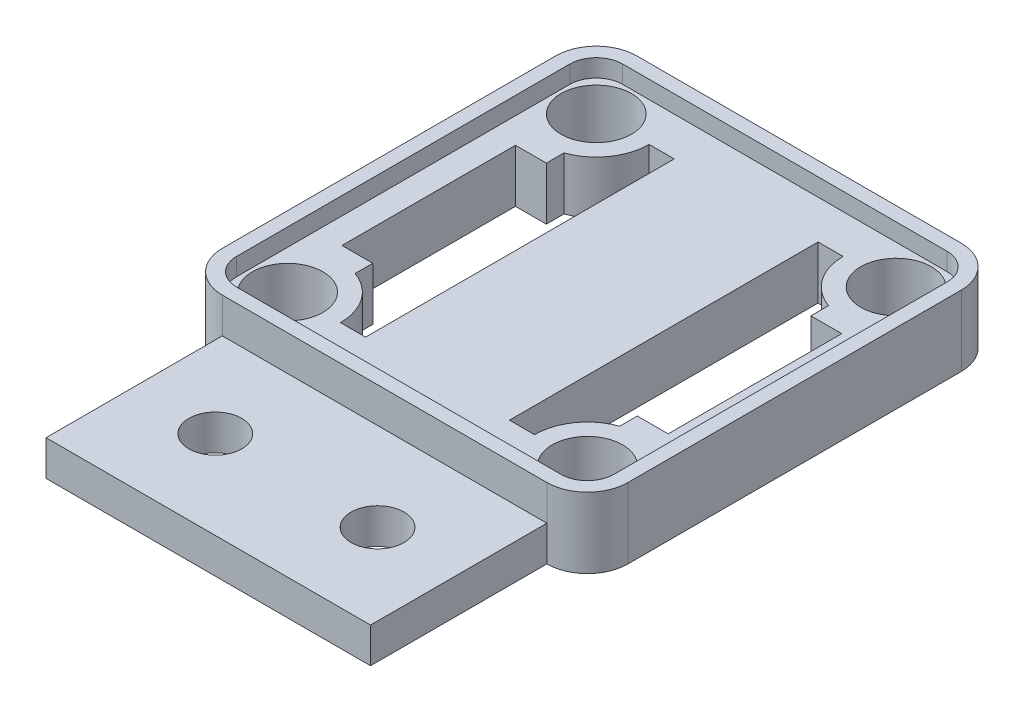
SolidWorks part; units mm, degrees
ref_plane "Front Plane" through (0, 0, 0) normal (0, 0, 1) x (1, 0, 0)
ref_plane "Top Plane" through (0, 0, 0) normal (0, 1, 0) x (1, 0, 0)
ref_plane "Right Plane" through (0, 0, 0) normal (1, 0, 0) x (0, 0, -1)
sketch "Sketch1" plane through (0, 0, 0) normal (0, 1, 0) x (1, 0, 0)
  line L1 (-12.6491, 14.6331) -> (5.7509, 14.6331)
  line L2 (-14.9491, 12.3331) -> (-14.9491, -6.5669)
  line L3 (-12.6491, -8.8669) -> (5.7509, -8.8669)
  line L4 (8.0509, 12.3331) -> (8.0509, -6.5669)
  line L5 (-14.9491, 14.6331) -> (8.0509, -8.8669) construction
  line L6 (-14.9491, -8.8669) -> (8.0509, 14.6331) construction
  arc A0 (8.0509, 12.3331) -> (5.7509, 14.6331) centre (5.7509, 12.3331) ccw
  arc A1 (-12.6491, -8.8669) -> (-14.9491, -6.5669) centre (-12.6491, -6.5669) cw
  arc A2 (5.7509, -8.8669) -> (8.0509, -6.5669) centre (5.7509, -6.5669) ccw
  arc A3 (-14.9491, 12.3331) -> (-12.6491, 14.6331) centre (-12.6491, 12.3331) cw
  point P0 (-3.4491, 2.8831)
  dimension "D3" = 2.3
  dimension "D4" = 2.3
  dimension "D1" = 23.5
  dimension "D2" = 23
extrude "Boss-Extrude1" add sketch "Sketch1" along normal blind 4
sketch "Sketch2" plane through (0, 4, 0) normal (0, 1, 0) x (1, 0, 0)
  line L8 (5.7509, 13.6331) -> (-12.6491, 13.6331)
  line L9 (-13.9491, 12.3331) -> (-13.9491, -6.5669)
  line L10 (-12.6491, -7.8669) -> (5.7509, -7.8669)
  line L11 (7.0509, -6.5669) -> (7.0509, 12.3331)
  line L12 (5.7509, 13.6331) -> (-12.6491, 13.6331)
  line L13 (-13.9491, 12.3331) -> (-13.9491, -6.5669)
  line L14 (-12.6491, -7.8669) -> (5.7509, -7.8669)
  line L15 (7.0509, -6.5669) -> (7.0509, 12.3331)
  arc A8 (7.0509, 12.3331) -> (5.7509, 13.6331) centre (5.7509, 12.3331) ccw
  arc A9 (-12.6491, 13.6331) -> (-13.9491, 12.3331) centre (-12.6491, 12.3331) ccw
  arc A10 (-13.9491, -6.5669) -> (-12.6491, -7.8669) centre (-12.6491, -6.5669) ccw
  arc A11 (5.7509, -7.8669) -> (7.0509, -6.5669) centre (5.7509, -6.5669) ccw
  arc A12 (7.0509, 12.3331) -> (5.7509, 13.6331) centre (5.7509, 12.3331) ccw
  arc A13 (-12.6491, 13.6331) -> (-13.9491, 12.3331) centre (-12.6491, 12.3331) ccw
  arc A14 (-13.9491, -6.5669) -> (-12.6491, -7.8669) centre (-12.6491, -6.5669) ccw
  arc A15 (5.7509, -7.8669) -> (7.0509, -6.5669) centre (5.7509, -6.5669) ccw
  dimension "D1" = 1
extrude "Cut-Extrude2" cut sketch "Sketch2" against normal blind 1
sketch "Sketch5" plane through (0, 3, 0) normal (0, 1, 0) x (1, 0, 0)
  line L0 (-3.4491, 13.6331) -> (-3.4491, -7.8669) construction
  line L1 (5.7509, 13.6331) -> (-12.6491, 13.6331) construction
  line L2 (-12.6491, -7.8669) -> (5.7509, -7.8669) construction
  line L3 (7.0509, 2.8831) -> (-13.9491, 2.8831) construction
  line L4 (7.0509, -6.5669) -> (7.0509, 12.3331) construction
  line L5 (-13.9491, 12.3331) -> (-13.9491, -6.5669) construction
  circle A0 centre (5.0509, 11.6331) radius 2
  circle A1 centre (5.0509, -5.8669) radius 2
  circle A2 centre (-11.9491, -5.8669) radius 2
  circle A3 centre (-11.9491, 11.6331) radius 2
  dimension "D1" = 4
extrude "Cut-Extrude3" cut sketch "Sketch5" against normal through all
sketch "Sketch6" plane through (0, 3, 0) normal (0, 1, 0) x (1, 0, 0)
  line L0 (-14.9491, 12.3331) -> (-14.9491, -6.5669) construction
  line L1 (8.0509, -6.5669) -> (8.0509, 12.3331) construction
  line L14 (4.0509, -5.8669) -> (4.0509, 11.6331)
  line L15 (4.0509, -3.0385) -> (4.0509, 8.8047)
  line L16 (2.0509, 11.6331) -> (2.0509, -5.8669)
  line L17 (-10.9491, 12.3331) -> (-10.9491, -6.5669)
  line L18 (-10.9491, 8.8047) -> (-10.9491, -3.0385)
  line L19 (-8.9491, 11.6331) -> (-8.9491, -5.8669)
  arc A5 (-11.9491, -8.8669) -> (-14.9491, -5.8669) centre (-11.9491, -5.8669) ccw
  arc A6 (-8.9491, -5.8669) -> (-10.9491, -3.0385) centre (-11.9491, -5.8669) ccw
  arc A20 (5.0509, 14.6331) -> (8.0509, 11.6331) centre (5.0509, 11.6331) ccw
  arc A21 (2.0509, 11.6331) -> (4.0509, 8.8047) centre (5.0509, 11.6331) ccw
  arc A23 (-14.9491, 11.6331) -> (-11.9491, 14.6331) centre (-11.9491, 11.6331) ccw
  arc A24 (-10.9491, 8.8047) -> (-8.9491, 11.6331) centre (-11.9491, 11.6331) ccw
  arc A26 (8.0509, -5.8669) -> (5.0509, -8.8669) centre (5.0509, -5.8669) ccw
  arc A27 (4.0509, -3.0385) -> (2.0509, -5.8669) centre (5.0509, -5.8669) ccw
  dimension "D1" = 23
  dimension "D2" = 1
  dimension "D3" = 1
  dimension "D4" = 1
  dimension "D5" = 1
  dimension "D6" = 3
  dimension "D7" = 3
extrude "Cut-Extrude4" cut sketch "Sketch6" against normal through all
sketch "Sketch7" plane through (0, 0, 8.8669) normal (0, 0, 1) x (1, 0, 0)
  line L0 (-14.9491, 4) -> (-14.9491, 0) construction
  line L1 (8.0509, 4) -> (8.0509, 0) construction
  line L2 (-12.6491, 4) -> (-12.6491, 0) construction
  line L3 (-12.6491, 2) -> (5.7509, 2)
  line L4 (5.7509, 4) -> (5.7509, 0) construction
  line L5 (5.7509, 2) -> (5.7509, 0)
  line L6 (5.7509, 0) -> (-12.6491, 0)
  line L7 (-12.6491, 0) -> (-12.6491, 2)
  dimension "D1" = 23
extrude "Boss-Extrude2" add sketch "Sketch7" along normal blind 10
sketch "Sketch8" plane through (0, 2, 0) normal (0, 1, 0) x (1, 0, 0)
  line L0 (-12.6491, -8.8669) -> (5.7509, -8.8669) construction
  line L1 (-12.6491, -18.8669) -> (-12.6491, -8.8669) construction
  line L2 (5.7509, -18.8669) -> (5.7509, -8.8669) construction
  line L3 (-3.4491, -8.8669) -> (-3.4491, -18.8669) construction
  line L4 (5.7509, -18.8669) -> (-12.6491, -18.8669) construction
  circle A0 centre (1.1509, -13.8669) radius 1.5
  circle A1 centre (-8.0491, -13.8669) radius 1.5
  dimension "D2" = 3
  dimension "D1" = 5
  dimension "D3" = 18.4
  dimension "D4" = 4.6
  dimension "D5" = 4.6
extrude "Cut-Extrude5" cut sketch "Sketch8" against normal through all
sketch "Sketch9" plane through (0, 4, 0) normal (0, 1, 0) x (1, 0, 0)
  line L8 (5.7509, 13.8331) -> (-12.6491, 13.8331)
  line L9 (-14.1491, 12.3331) -> (-14.1491, -6.5669)
  line L10 (-12.6491, -8.0669) -> (5.7509, -8.0669)
  line L11 (7.2509, -6.5669) -> (7.2509, 12.3331)
  line L12 (5.7509, 13.8331) -> (-12.6491, 13.8331)
  line L13 (-14.1491, 12.3331) -> (-14.1491, -6.5669)
  line L14 (-12.6491, -8.0669) -> (5.7509, -8.0669)
  line L15 (7.2509, -6.5669) -> (7.2509, 12.3331)
  arc A8 (7.2509, 12.3331) -> (5.7509, 13.8331) centre (5.7509, 12.3331) ccw
  arc A9 (-12.6491, 13.8331) -> (-14.1491, 12.3331) centre (-12.6491, 12.3331) ccw
  arc A10 (-14.1491, -6.5669) -> (-12.6491, -8.0669) centre (-12.6491, -6.5669) ccw
  arc A11 (5.7509, -8.0669) -> (7.2509, -6.5669) centre (5.7509, -6.5669) ccw
  arc A12 (7.2509, 12.3331) -> (5.7509, 13.8331) centre (5.7509, 12.3331) ccw
  arc A13 (-12.6491, 13.8331) -> (-14.1491, 12.3331) centre (-12.6491, 12.3331) ccw
  arc A14 (-14.1491, -6.5669) -> (-12.6491, -8.0669) centre (-12.6491, -6.5669) ccw
  arc A15 (5.7509, -8.0669) -> (7.2509, -6.5669) centre (5.7509, -6.5669) ccw
  dimension "D1" = 0.8
extrude "Cut-Extrude6" cut sketch "Sketch9" against normal blind 1
sketch "Sketch11" plane through (0, 3, 0) normal (0, 1, 0) x (1, 0, 0)
  line L0 (-8.9491, 11.6331) -> (-7.528, 11.6331)
  line L1 (-7.528, 11.6331) -> (-7.528, -5.8669)
  line L2 (-7.528, -5.8669) -> (-8.9491, -5.8669)
  line L3 (-8.9491, -5.8669) -> (-8.9491, 11.6331)
  line L4 (-3.4491, 13.8331) -> (-3.4491, -8.0669) construction
  line L5 (5.7509, 13.8331) -> (-12.6491, 13.8331) construction
  line L6 (-12.6491, -8.0669) -> (5.7509, -8.0669) construction
  line L7 (0.6299, -5.8669) -> (2.0509, -5.8669)
  line L8 (0.6299, 11.6331) -> (0.6299, -5.8669)
  line L9 (2.0509, 11.6331) -> (0.6299, 11.6331)
  line L10 (2.0509, -5.8669) -> (2.0509, 11.6331)
  line L11 (-10.9491, 8.8047) -> (-10.9491, -3.0385) construction
  line L12 (-12.6991, 7.8031) -> (-10.9491, 7.8031)
  line L13 (-12.6991, 7.8031) -> (-12.6991, -2.0369)
  line L14 (-12.6991, -2.0369) -> (-10.9491, -2.0369)
  line L15 (-10.9491, 7.8031) -> (-10.9491, -2.0369)
  line L16 (5.8009, -2.0369) -> (4.0509, -2.0369)
  line L17 (4.0509, 7.8031) -> (4.0509, -2.0369)
  line L18 (5.8009, 7.8031) -> (4.0509, 7.8031)
  line L19 (5.8009, 7.8031) -> (5.8009, -2.0369)
  point P22 (-10.9491, 2.8831)
  point P23 (-10.9491, 2.8831)
  point P24 (-12.7061, -2.0369)
  dimension "D1" = 9.84
  dimension "D2" = 1.75
extrude "Cut-Extrude7" cut sketch "Sketch11" against normal through all
